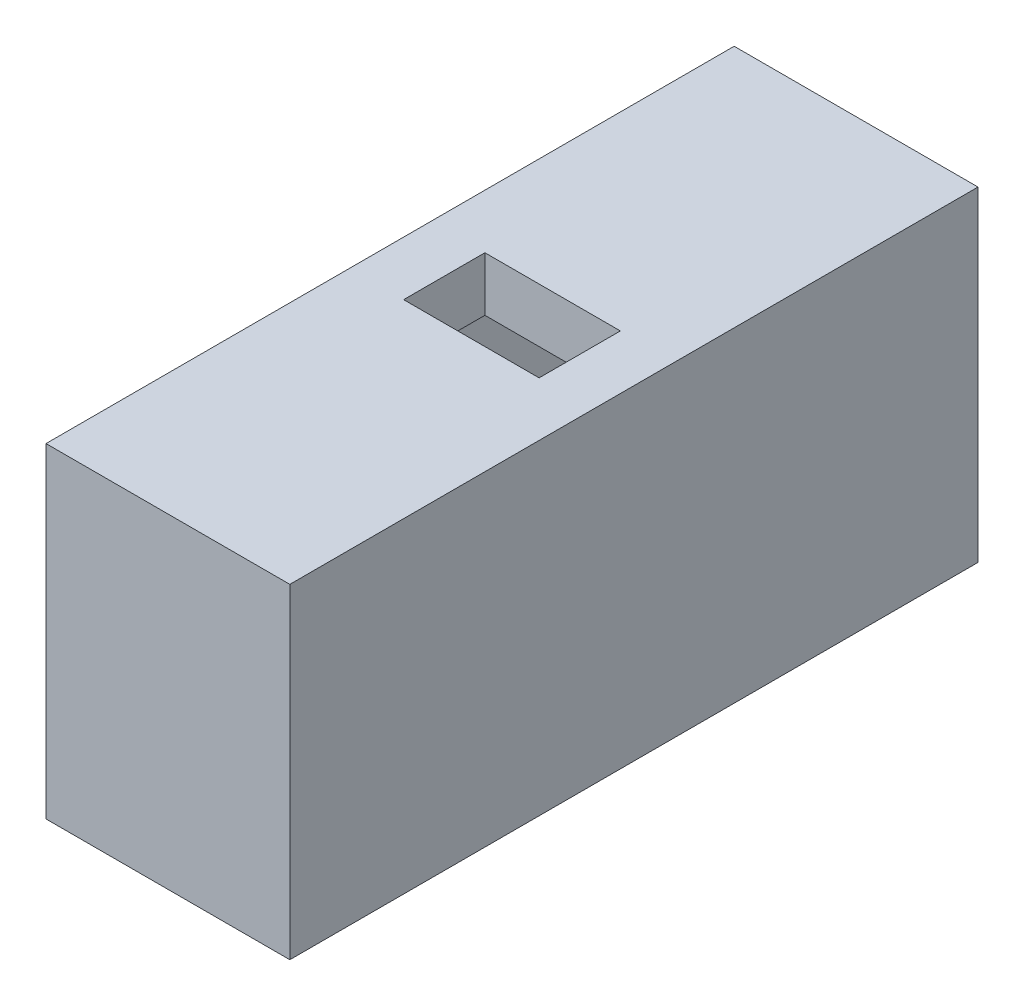
SolidWorks part; units mm, degrees
ref_plane "Front Plane" through (0, 0, 0) normal (0, 0, 1) x (1, 0, 0)
ref_plane "Top Plane" through (0, 0, 0) normal (0, 1, 0) x (1, 0, 0)
ref_plane "Right Plane" through (0, 0, 0) normal (1, 0, 0) x (0, 0, -1)
sketch "Sketch1" plane through (0, 0, 0) normal (0, 1, 0) x (1, 0, 0)
  line L1 (0, 0) -> (-9, 0)
  line L2 (0, 0) -> (0, 25.4)
  line L3 (0, 25.4) -> (-9, 25.4)
  line L4 (-9, 0) -> (-9, 25.4)
  line L5 (0, 0) -> (-9, 25.4) construction
  line L6 (0, 25.4) -> (-9, 0) construction
  point P4 (-4.5, 12.7)
  dimension "D1" = 25.4
  dimension "D2" = 9
extrude "Boss-Extrude1" add sketch "Sketch1" along normal blind 12
sketch "Sketch2" plane through (0, 12, 0) normal (0, 1, 0) x (1, 0, 0)
  line L0 (-4.5, 0) -> (-4.5, 25.4) construction
  line L2 (-9, 0) -> (0, 0) construction
  line L7 (0, 25.4) -> (-9, 25.4) construction
  line L9 (-2, 11.2) -> (-7, 11.2)
  line L10 (-2, 11.2) -> (-2, 14.2)
  line L11 (-2, 14.2) -> (-7, 14.2)
  line L12 (-7, 11.2) -> (-7, 14.2)
  line L13 (-2, 11.2) -> (-7, 14.2) construction
  line L14 (-2, 14.2) -> (-7, 11.2) construction
  point P7 (-4.5, 12.7)
  dimension "D1" = 5
  dimension "D2" = 3
extrude "Cut-Extrude1" cut sketch "Sketch2" against normal through all
sketch "Sketch4" plane through (0, 0, -25.4) normal (0, 0, -1) x (-1, 0, 0)
  line L0 (9, 6) -> (0, 6) construction
  line L1 (9, 12) -> (9, 0) construction
  line L2 (0, 12) -> (0, 0) construction
  line L4 (1.75, 10) -> (7.25, 10)
  line L5 (1.75, 10) -> (1.75, 2)
  line L6 (1.75, 2) -> (7.25, 2)
  line L7 (7.25, 10) -> (7.25, 2)
  line L8 (1.75, 10) -> (7.25, 2) construction
  line L9 (1.75, 2) -> (7.25, 10) construction
  point P6 (4.5, 6)
  dimension "D1" = 5.5
  dimension "D2" = 8
extrude "Cut-Extrude2" cut sketch "Sketch4" against normal blind 22
sketch "Sketch7" plane through (0, 0, -3.4) normal (0, 0, -1) x (-1, 0, 0)
  line L0 (1.75, 6) -> (7.25, 6) construction
  line L1 (1.75, 10) -> (1.75, 2) construction
  line L2 (7.25, 2) -> (7.25, 10) construction
  line L4 (7.25, 2) -> (1.75, 2)
  line L5 (7.25, 2) -> (7.25, 10)
  line L6 (7.25, 10) -> (1.75, 10)
  line L7 (1.75, 2) -> (1.75, 10)
  line L8 (7.25, 2) -> (1.75, 10) construction
  line L9 (7.25, 10) -> (1.75, 2) construction
  circle A0 centre (4.5, 6) radius 2.235
  dimension "D1" = 4.47
extrude "Boss-Extrude3" add sketch "Sketch7" along normal up to surface (7.8 mm away) up to face at (-4.5, 1, -11.2)
sketch "Sketch8" plane through (0, 0, -3.4) normal (0, 0, -1) x (-1, 0, 0)
  line L0 (2.265, 6) -> (6.735, 6) construction
  circle A0 centre (4.5, 6) radius 2.235 construction
  circle A1 centre (4.5, 6) radius 2.235
extrude "Boss-Extrude4" add sketch "Sketch8" along normal blind 3.4162
